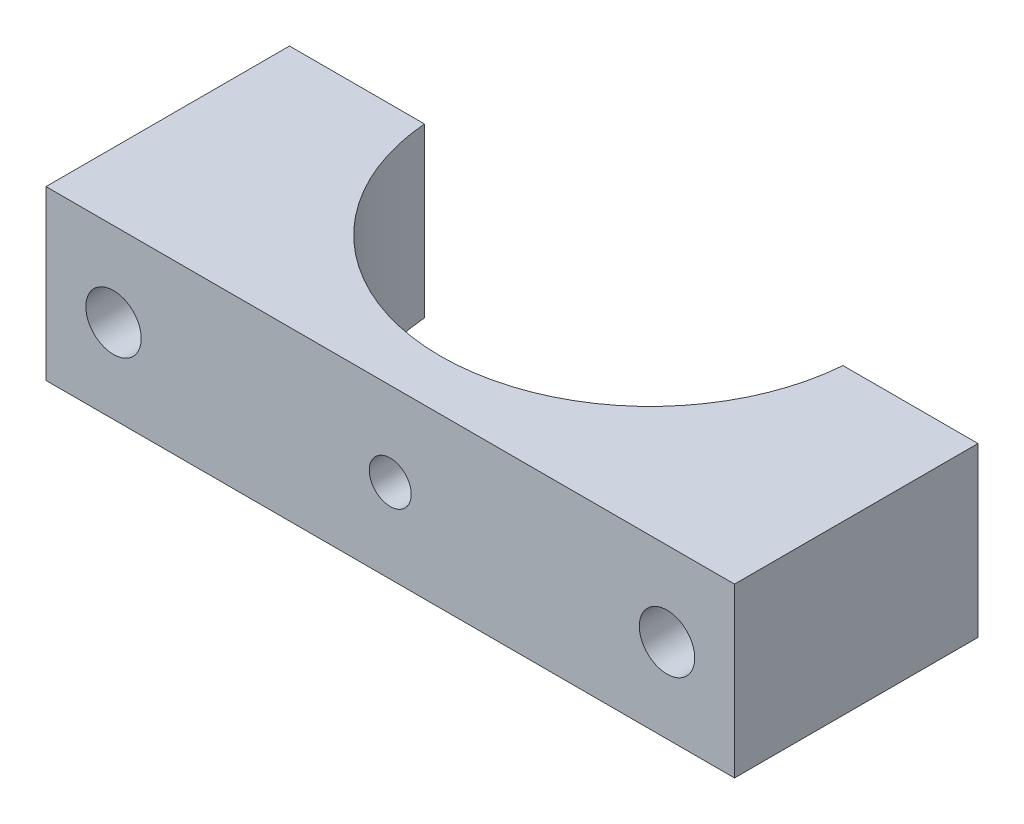
SolidWorks part; units mm, degrees
material "3.1355 (EN-AW 2024)"
ref_plane "Front" through (0, 0, 0) normal (0, 0, 1) x (1, 0, 0)
ref_plane "Top" through (0, 0, 0) normal (0, 1, 0) x (1, 0, 0)
ref_plane "Right" through (0, 0, 0) normal (1, 0, 0) x (0, 0, -1)
sketch "Эскиз1" plane through (0, 0, 0) normal (0, 1, 0) x (1, 0, 0)
  line L0 (0, 0) -> (41, 0)
  line L1 (20.5, 0) -> (20.5, 15.5) construction
  line L2 (0, 0) -> (0, 14.5)
  line L3 (41, 0) -> (41, 14.5)
  line L4 (0, 14.5) -> (8.0401, 14.5)
  line L5 (41, 14.5) -> (32.9599, 14.5)
  arc A0 (8.0401, 14.5) -> (32.9599, 14.5) centre (20.5, 15.5) ccw
  point P5 (20.5, 3)
  dimension "D2" = 25
  dimension "D1" = 41
  dimension "D3" = 15.5
  dimension "D4" = 14.5
extrude "Бобышка-Вытянуть1" add sketch "Эскиз1" along normal blind 10
sketch "Эскиз2" plane through (0, 0, -14.5) normal (0, 0, -1) x (-1, 0, 0)
  line L0 (-41, 5) -> (-32.9599, 5) construction
  line L1 (-41, 10) -> (-41, 0) construction
  line L2 (-32.9599, 10) -> (-32.9599, 0) construction
  line L3 (-20.5, 10) -> (-20.5, 0) construction
  line L4 (-8.0401, 10) -> (-32.9599, 10) construction
  line L5 (-32.9599, 0) -> (-8.0401, 0) construction
  line L6 (-8.0401, 5) -> (0, 5) construction
  line L7 (-8.0401, 10) -> (-8.0401, 0) construction
  line L8 (0, 10) -> (0, 0) construction
  point P18 (-36.98, 5)
  point P19 (-4.02, 5)
hole_wizard "Отверстие обработанное метчиком M4x0.71" positions "Эскиз4" profile "Эскиз3" tap size "M4x0.7" standard "Ansi Metric" end condition through all
sketch "Эскиз4" plane through (0, 0, -14.5) normal (0, 0, -1) x (-1, 0, 0)
  point P0 (-36.98, 5)
  point P3 (-4.02, 5)
sketch "Эскиз3" plane through (36.98, 5, -14.5) normal (1, 0, 0) x (0, 1, 0)
  line L0 (0, 0) -> (0, 14.5)
  line L1 (0, 14.5) -> (1.65, 14.5)
  line L2 (1.65, 14.5) -> (1.65, 0)
  line L5 (1.65, 0) -> (0, 0)
  line L11 (0, -6.35) -> (0, 107.95) construction
  dimension "Диаметр проходного сверла" = 3.3
  dimension "Глубина проходного сверла" = 14.5
cosmetic thread "Отверстие резьбы1" parameters "D2"=4
cosmetic thread "Отверстие резьбы2" parameters "D2"=4
sketch "Эскиз5" plane through (0, 0, 0) normal (0, 0, 1) x (1, 0, 0)
  line L0 (0, 5) -> (41, 5) construction
  line L1 (0, 10) -> (0, 0) construction
  line L2 (41, 10) -> (41, 0) construction
  point P6 (20.5, 5)
hole_wizard "Отверстие обработанное метчиком M3x0.51" positions "Эскиз7" profile "Эскиз6" tap size "M3x0.5" standard "Ansi Metric" end condition through all
sketch "Эскиз7" plane through (0, 0, 0) normal (0, 0, 1) x (1, 0, 0)
  point P0 (20.5, 5)
sketch "Эскиз6" plane through (20.5, 5, 0) normal (1, 0, 0) x (0, -1, 0)
  line L0 (0, 0) -> (0, 14.5)
  line L1 (0, 14.5) -> (1.25, 14.5)
  line L2 (1.25, 14.5) -> (1.25, 0)
  line L5 (1.25, 0) -> (0, 0)
  line L11 (0, -6.35) -> (0, 107.95) construction
  dimension "Диаметр проходного сверла" = 2.5
  dimension "Глубина проходного сверла" = 14.5
cosmetic thread "Отверстие резьбы3" parameters "D2"=3
equation "\"D3@Эскиз1\"=3+\"D2@Эскиз1\"/2"
equation "\"D4@Эскиз1\"=3+\"D2@Эскиз1\"/2-1"
